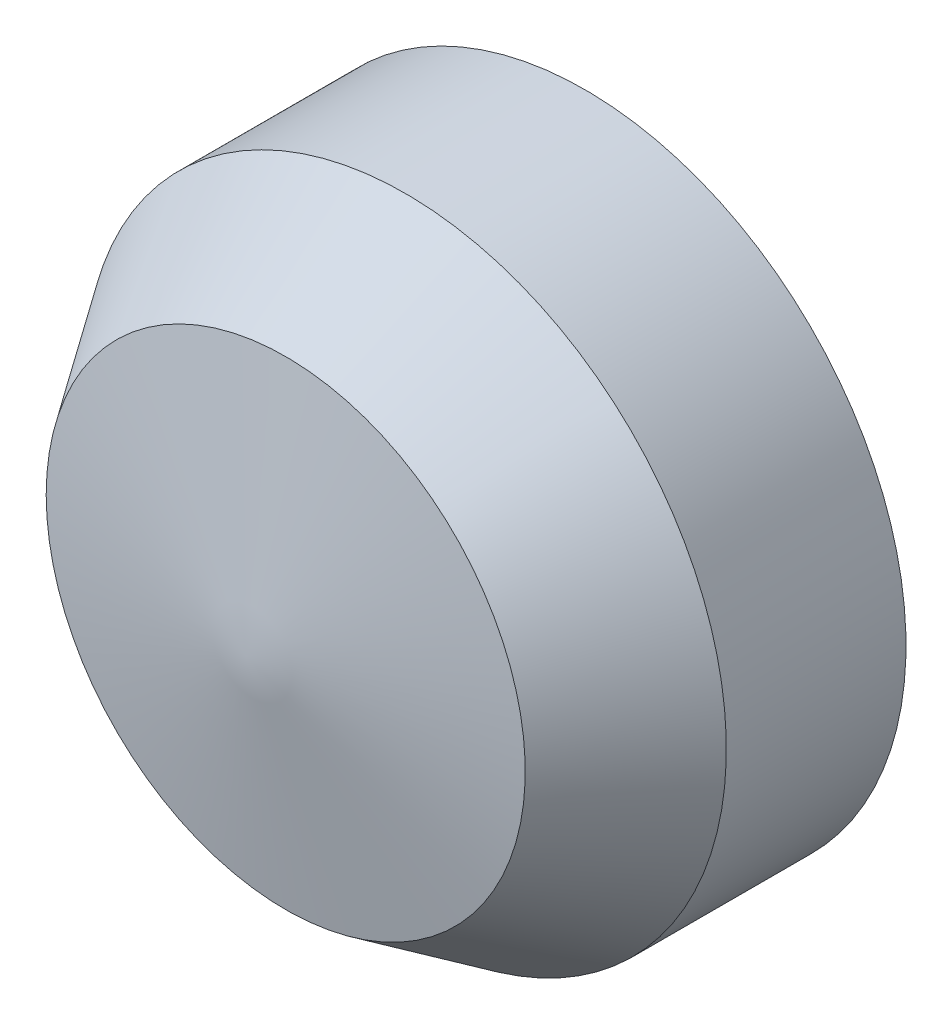
SolidWorks part; units mm, degrees
material "POM Acetal Copolymer"
ref_plane "Front Plane" through (0, 0, 0) normal (0, 0, 1) x (1, 0, 0)
ref_plane "Top Plane" through (0, 0, 0) normal (0, 1, 0) x (1, 0, 0)
ref_plane "Right Plane" through (0, 0, 0) normal (1, 0, 0) x (0, 0, -1)
sketch "Revolve profile 1" plane through (0, 0, 0) normal (0, 1, 0) x (1, 0, 0)
  line L0 (0, -34) -> (0, 0)
  line L1 (0, 0) -> (32.15, 0)
  line L2 (32.15, 0) -> (32.15, -18)
  line L3 (32.15, -18) -> (24, -30)
  line L4 (24, -30) -> (0, -34)
  line L5 (0, 5) -> (0, -39) construction
  dimension "D1" = 8.15
  dimension "D2" = 32.15
  dimension "D3" = 18
  dimension "D4" = 30
  dimension "D5" = 34
revolve "Revolve 1" add sketch "Revolve profile 1" angle 360 about L5
